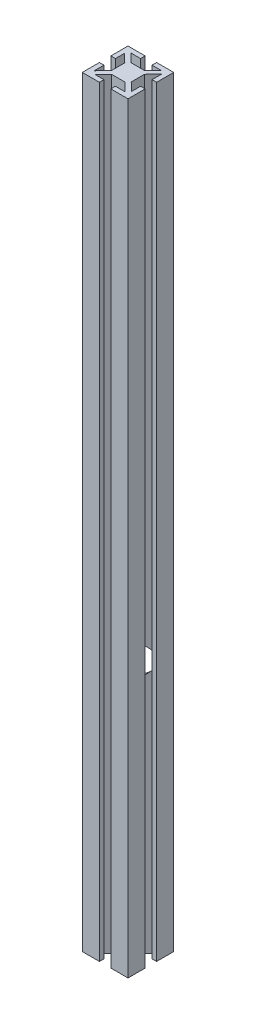
SolidWorks part; units mm, degrees
material "1060 Alloy"
ref_plane "Front Plane" through (0, 0, 0) normal (0, 0, 1) x (1, 0, 0)
ref_plane "Top Plane" through (0, 0, 0) normal (0, 1, 0) x (1, 0, 0)
ref_plane "Right Plane" through (0, 0, 0) normal (1, 0, 0) x (0, 0, -1)
sketch "Sketch1" plane through (0, 0, 0) normal (0, 1, 0) x (1, 0, 0)
  line L1 (-10, 10) -> (10, 10) construction
  line L2 (-10, 10) -> (-10, -10) construction
  line L3 (-10, -10) -> (10, -10) construction
  line L4 (10, 10) -> (10, -10) construction
  line L5 (-10, 10) -> (10, -10) construction
  line L6 (-10, -10) -> (10, 10) construction
  circle A0 centre (0, 0) radius 2
  point P0 (0, 0)
  dimension "D3" = 4
  dimension "D1" = 20
  dimension "D2" = 20
sketch "Sketch2" plane through (0, 0, 0) normal (0, 1, 0) x (1, 0, 0)
  line L0 (-10, 2.5) -> (-10, -2.5) construction
  line L1 (-10, 10) -> (-10, -10) construction
  line L2 (-10, -10) -> (-10, -2.5)
  line L3 (-10, -2.5) -> (-8, -2.5)
  line L4 (-8, -2.5) -> (-8, -6.7683)
  line L5 (-8, -6.7683) -> (-4.3583, -2.9445)
  line L6 (-4.3583, -2.9445) -> (-2.91, -4.3238)
  line L7 (-2.91, -4.3238) -> (-6.4243, -8)
  line L8 (-6.4243, -8) -> (-2.5, -8)
  line L9 (-2.5, -8) -> (-2.5, -10)
  line L10 (-10, -10) -> (10, -10) construction
  line L11 (-2.5, -10) -> (-10, -10)
  line L12 (-2.5, -10) -> (2.5, -10) construction
  line L14 (-10, -10) -> (10, 10) construction
  line L15 (-10, 2.5) -> (-10, 10)
  line L16 (-10, 10) -> (-2.5, 10)
  line L17 (-2.5, 10) -> (-2.5, 8)
  line L18 (-2.5, 8) -> (-6.7683, 8)
  line L19 (-6.7683, 8) -> (-2.9445, 4.3583)
  line L20 (-2.9445, 4.3583) -> (-4.3238, 2.91)
  line L21 (-4.3238, 2.91) -> (-8, 6.4243)
  line L22 (-8, 6.4243) -> (-8, 2.5)
  line L23 (-8, 2.5) -> (-10, 2.5)
  line L24 (2.5, 10) -> (10, 10)
  line L25 (10, 10) -> (10, 2.5)
  line L26 (10, 2.5) -> (8, 2.5)
  line L27 (8, 2.5) -> (8, 6.7683)
  line L28 (8, 6.7683) -> (4.3583, 2.9445)
  line L29 (4.3583, 2.9445) -> (2.91, 4.3238)
  line L30 (2.91, 4.3238) -> (6.4243, 8)
  line L31 (6.4243, 8) -> (2.5, 8)
  line L32 (2.5, 8) -> (2.5, 10)
  line L33 (10, -2.5) -> (10, -10)
  line L34 (10, -10) -> (2.5, -10)
  line L35 (2.5, -10) -> (2.5, -8)
  line L36 (2.5, -8) -> (6.7683, -8)
  line L37 (6.7683, -8) -> (2.9445, -4.3583)
  line L38 (2.9445, -4.3583) -> (4.3238, -2.91)
  line L39 (4.3238, -2.91) -> (8, -6.4243)
  line L40 (8, -6.4243) -> (8, -2.5)
  line L41 (8, -2.5) -> (10, -2.5)
  line L42 (-10, 10) -> (10, -10) construction
  line L43 (-4.3238, 4.3238) -> (4.3238, 4.3238)
  line L44 (-4.3238, 4.3238) -> (-4.3238, -4.3238)
  line L45 (-4.3238, -4.3238) -> (4.3238, -4.3238)
  line L46 (4.3238, 4.3238) -> (4.3238, -4.3238)
  line L47 (-4.3238, 4.3238) -> (4.3238, -4.3238) construction
  line L48 (-4.3238, -4.3238) -> (4.3238, 4.3238) construction
  point P5 (-10, 0)
  point P11 (0, 0)
  point P14 (-3.6341, -3.6341)
  point P19 (0, -10)
  dimension "D1" = 5
  dimension "D2" = 5
  dimension "D3" = 2
  dimension "D4" = 2
  dimension "D5" = 2
  dimension "D6" = 2
  dimension "D7" = 9
  dimension "D8" = 4
extrude "Boss-Extrude1" add sketch "Sketch2" along normal blind 333 contours L45 L44 L6 L5 L4 L3 L2 L11 L9 L8 L7 | L46 L29 L43 L20 L44 L6 L45 L38 | L39 L46 L45 L38 L37 L36 L35 L34 L33 L41 L40 | L43 L46 L29 L28 L27 L26 L25 L24 L32 L31 L30 | L44 L43 L20 L19 L18 L17 L16 L15 L23 L22 L21 | L46 L38 L45 | L46 L43 L29
sketch "Sketch4" plane through (10, 0, 0) normal (1, 0, 0) x (0, 0, -1)
  line L0 (0.0337, 333) -> (0.0337, 281.6) construction
  line L1 (2.9773, 333) -> (-2.91, 333) construction
  line L2 (0.0337, 281.6) -> (0.0337, 268.6) construction
  line L3 (0.0337, 268.6) -> (0.0337, 248.6) construction
  circle A0 centre (0.0337, 281.6) radius 2
  circle A1 centre (0.0337, 268.6) radius 2
  circle A2 centre (0.0337, 248.6) radius 2
  dimension "D2" = 4
  dimension "D5" = 4
  dimension "D6" = 4
  dimension "D1" = 51.4
  dimension "D3" = 13
  dimension "D4" = 20
extrude "Cut-Extrude1" [suppressed] cut sketch "Sketch4" against normal blind 110 contours A1 | A2 | A0
sketch "Sketch5" plane through (0, 0, -10) normal (0, 0, -1) x (-1, 0, 0)
  line L0 (0.0337, 333) -> (0.0337, 293.49) construction
  line L1 (2.9773, 333) -> (-2.91, 333) construction
  circle A0 centre (0.0337, 293.49) radius 4.5
  dimension "D2" = 9
  dimension "D1" = 39.51
extrude "Cut-Extrude2" [suppressed] cut sketch "Sketch5" against normal blind 110 contours A0
sketch "Sketch7" [suppressed] plane through (0, 0, -10) normal (0, 0, -1) x (-1, 0, 0)
  line L0 (0, 0) -> (0, 28) construction
  line L1 (6.5, 21.8611) -> (-6.5, 21.8611) construction
  line L2 (6.5, 6.8611) -> (-6.5, 6.8611) construction
  line L3 (-6.5, 6.8611) -> (-6.5, 21.8611) construction
  line L4 (6.5, 21.8611) -> (6.5, 6.8611) construction
  line L5 (10, 320) -> (10, 0) construction
  circle A0 centre (6.5, 21.8611) radius 2.1
  circle A1 centre (6.5, 6.8611) radius 2.1
  circle A2 centre (-6.5, 21.8611) radius 2.1
  circle A3 centre (-6.5, 6.8611) radius 2.1
  point P6 (0, 21.8611)
  point P9 (0, 6.8611)
  dimension "D3" = 4.2
  dimension "D4" = 4.2
  dimension "D1" = 28
  dimension "D2" = 3.5
  dimension "D5" = 15
sketch "Sketch9" plane through (-10, 0, 0) normal (-1, 0, 0) x (0, 0, 1)
  line L0 (0, 0) -> (0, 28) construction
  line L1 (6.5, 6) -> (-6.5, 6) construction
  line L2 (-6.5, 6) -> (-6.5, 21) construction
  line L3 (-6.5, 21) -> (6.5, 21) construction
  line L4 (6.5, 21) -> (6.5, 6) construction
  line L5 (10, 333) -> (10, 0) construction
  line L6 (-10, 0) -> (10, 0) construction
  circle A0 centre (6.5, 6) radius 2.1
  circle A1 centre (6.5, 21) radius 2.1
  circle A2 centre (-6.5, 21) radius 2.1
  circle A3 centre (-6.5, 6) radius 2.1
  point P6 (0, 6)
  dimension "D2" = 4.2
  dimension "D1" = 28
  dimension "D3" = 15
  dimension "D4" = 3.5
  dimension "D5" = 6
extrude "Cut-Extrude4" [suppressed] cut sketch "Sketch9" against normal through all
sketch "Sketch10" plane through (0, 0, -10) normal (0, 0, -1) x (-1, 0, 0)
  line L0 (0, 0) -> (0, 111) construction
  circle A0 centre (0, 111) radius 7
  dimension "D2" = 14
  dimension "D1" = 111
extrude "Cut-Extrude5" cut sketch "Sketch10" against normal blind 10
sketch "Sketch11" plane through (0, 0, 10) normal (0, 0, 1) x (1, 0, 0)
  line L0 (0.0337, 333) -> (0.0337, 325) construction
  line L1 (-2.91, 333) -> (2.9773, 333) construction
  circle A0 centre (0.0337, 325) radius 2
  dimension "D2" = 4
  dimension "D1" = 8
extrude "Cut-Extrude6" cut sketch "Sketch11" against normal blind 50
sketch "Sketch12" plane through (0, 0, 10) normal (0, 0, 1) x (1, 0, 0)
  circle A0 centre (0, 111) radius 2
  circle A1 centre (0, 111) radius 7
  circle A2 centre (0, 111) radius 7 construction
  dimension "D2" = 4
  dimension "D1" = 0
extrude "Cut-Extrude7" cut sketch "Sketch12" against normal blind 50 contours A0
sketch "Sketch13" plane through (0, 0, 10) normal (0, 0, 1) x (1, 0, 0)
  line L0 (0, 0) -> (0, 10) construction
  circle A0 centre (0, 10) radius 2
  dimension "D2" = 4
  dimension "D1" = 10
extrude "Cut-Extrude8" cut sketch "Sketch13" against normal blind 50 contours A0
sketch "Sketch14" plane through (0, 0, 10) normal (0, 0, 1) x (1, 0, 0)
  line L0 (0, 0) -> (0, 10) construction
  line L1 (0, 10) -> (0, 111) construction
  line L2 (0, 111) -> (0.0337, 325) construction
  line L3 (0.0337, 325) -> (0.0337, 333) construction
  line L4 (-2.91, 333) -> (2.9773, 333) construction
  dimension "D1" = 8
  dimension "D2" = 214
  dimension "D3" = 101
sketch "Sketch15" plane through (-10, 0, 0) normal (-1, 0, 0) x (0, 0, 1)
  line L0 (0, 105.495) -> (0, 116.505) construction
  line L1 (-10, 110.9634) -> (0, 111) construction
  line L2 (-10, 333) -> (-10, 0) construction
  dimension "D1" = 10
sketch "Sketch17" plane through (0, 0, -10) normal (0, 0, -1) x (-1, 0, 0)
  circle A0 centre (0, 111) radius 7
  dimension "D1" = 14
